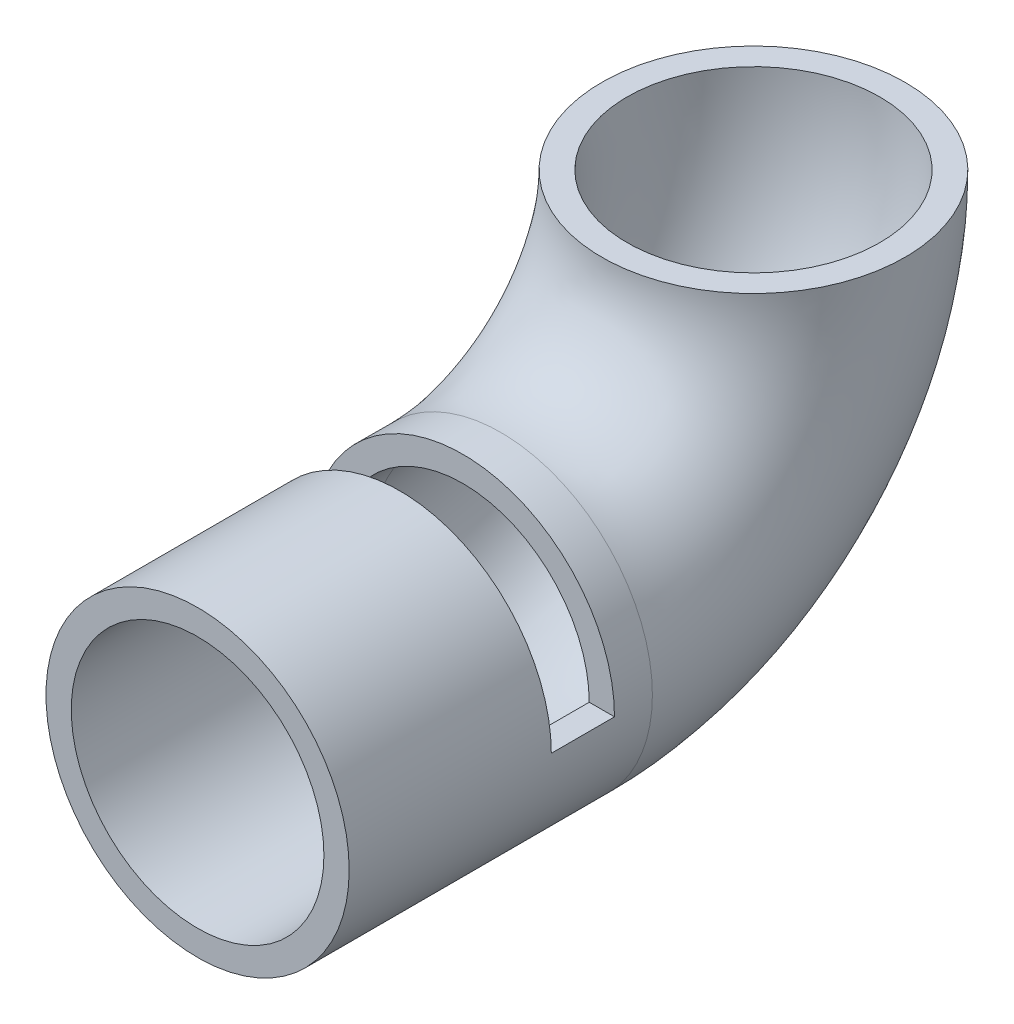
SolidWorks part; units mm, degrees
material "Plain Carbon Steel"
ref_plane "Front Plane" through (0, 0, 0) normal (0, 0, 1) x (1, 0, 0)
ref_plane "Top Plane" through (0, 0, 0) normal (0, 1, 0) x (1, 0, 0)
ref_plane "Right Plane" through (0, 0, 0) normal (1, 0, 0) x (0, 0, -1)
sketch "Sketch1" plane through (0, 0, 0) normal (0, 0, 1) x (1, 0, 0)
  circle A0 centre (0, 0) radius 15.875
  circle A1 centre (0, 0) radius 19.05
  dimension "D1" = 31.75
  dimension "D2" = 3.175
sketch "Sketch2" plane through (0, 0, 0) normal (1, 0, 0) x (0, 0, -1)
  line L0 (0, 0) -> (38.1, 0)
  line L1 (0, 19.05) -> (0, -19.05) construction
  line L2 (69.85, 31.75) -> (69.85, 0) construction
  line L3 (69.85, 0) -> (38.1, 0) construction
  arc A0 (38.1, 0) -> (69.85, 31.75) centre (38.1, 31.75) ccw
  point P8 (45.0815, 0.0116)
  dimension "D1" = 38.1
  dimension "D2" = 31.75
sweep "Sweep1" add profiles "Sketch1" path "Sketch2"
ref_plane "Plane1" through (0, 0, -25.4) normal (0, 0, 1) x (1, 0, 0)
sketch "Sketch3" plane through (0, 0, -25.4) normal (0, 0, 1) x (1, 0, 0)
  line L0 (-19.05, 0) -> (-15.875, 0)
  line L1 (15.875, 0) -> (19.05, 0)
  circle A0 centre (0, 0) radius 15.875 construction
  circle A1 centre (0, 0) radius 19.05
  arc A2 (19.05, 0) -> (-19.05, 0) centre (0, 0) ccw
  arc A3 (15.875, 0) -> (-15.875, 0) centre (0, 0) ccw
  dimension "D1" = 0
extrude "Cut-Extrude1" cut sketch "Sketch3" against normal blind 7.9375
ref_plane "Plane2" through (0, 0, -19.05) normal (0, 0, 1) x (1, 0, 0)
ref_plane "Plane3" through (0, -19.05, 0) normal (0, -1, 0) x (-1, 0, 0)
ref_plane "Plane4" through (0, -20.1625, 0) normal (0, -1, 0) x (-1, 0, 0)
